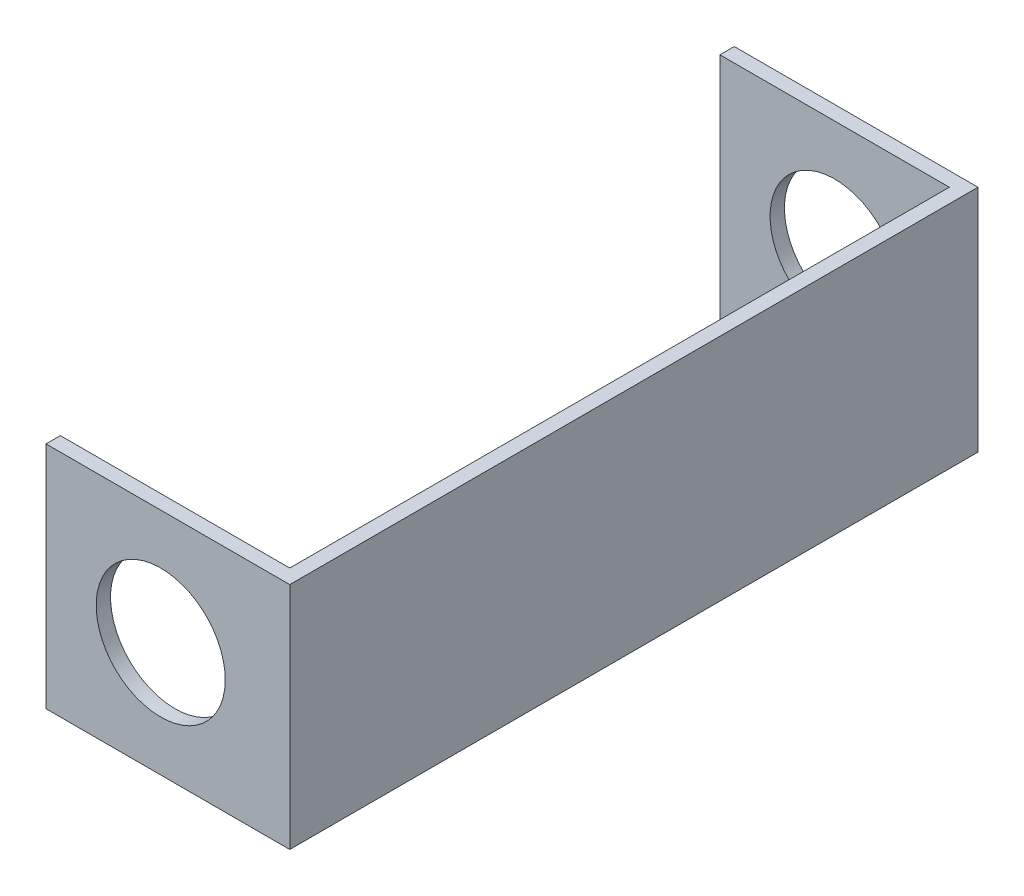
SolidWorks part; units mm, degrees
ref_plane "Front Plane" through (0, 0, 0) normal (0, 0, 1) x (1, 0, 0)
ref_plane "Top Plane" through (0, 0, 0) normal (0, 1, 0) x (1, 0, 0)
ref_plane "Right Plane" through (0, 0, 0) normal (1, 0, 0) x (0, 0, -1)
sketch "Sketch1" plane through (0, 0, 0) normal (0, 0, 1) x (1, 0, 0)
  line L1 (0, 0) -> (53.975, 0)
  line L2 (0, 0) -> (0, -50.8)
  line L3 (0, -50.8) -> (53.975, -50.8)
  line L4 (53.975, 0) -> (53.975, -50.8)
  circle A0 centre (25.4, -25.4) radius 14.2875
  dimension "D5" = 28.575
  dimension "D1" = 50.8
  dimension "D2" = 53.975
  dimension "D3" = 25.4
  dimension "D4" = 25.4
extrude "Boss-Extrude1" add sketch "Sketch1" along normal blind 3.175
sketch "Sketch2" plane through (0, 0, 3.175) normal (0, 0, 1) x (1, 0, 0)
  line L0 (0, -50.8) -> (53.975, -50.8) construction
  line L1 (53.975, 0) -> (50.8, 0)
  line L2 (53.975, 0) -> (53.975, -50.8)
  line L3 (53.975, -50.8) -> (50.8, -50.8)
  line L4 (50.8, 0) -> (50.8, -50.8)
  dimension "D1" = 3.175
extrude "Boss-Extrude2" add sketch "Sketch2" along normal blind 146.05
sketch "Sketch3" plane through (0, 0, 149.225) normal (0, 0, 1) x (1, 0, 0)
  line L8 (50.8, -50.8) -> (50.8, 0)
  line L9 (50.8, 0) -> (0, 0)
  line L10 (0, 0) -> (0, -50.8)
  line L11 (0, -50.8) -> (50.8, -50.8)
  line L12 (50.8, -50.8) -> (50.8, 0)
  line L13 (50.8, 0) -> (0, 0)
  line L14 (0, 0) -> (0, -50.8)
  line L15 (0, -50.8) -> (50.8, -50.8)
  circle A0 centre (25.4, -25.4) radius 14.2875 construction
  circle A1 centre (25.4, -25.4) radius 14.2875
  line M7 (53.975, -50.8) -> (53.975, 0)
  line M8 (53.975, 0) -> (50.8, 0)
  line M9 (50.8, 0) -> (50.8, -50.8)
  line M10 (50.8, -50.8) -> (53.975, -50.8)
  dimension "D1" = 0
extrude "Boss-Extrude3" add sketch "Sketch3" along normal blind 3.175 contours M10 M7 M8 M9 | L14 L15 L13 A1 M9
